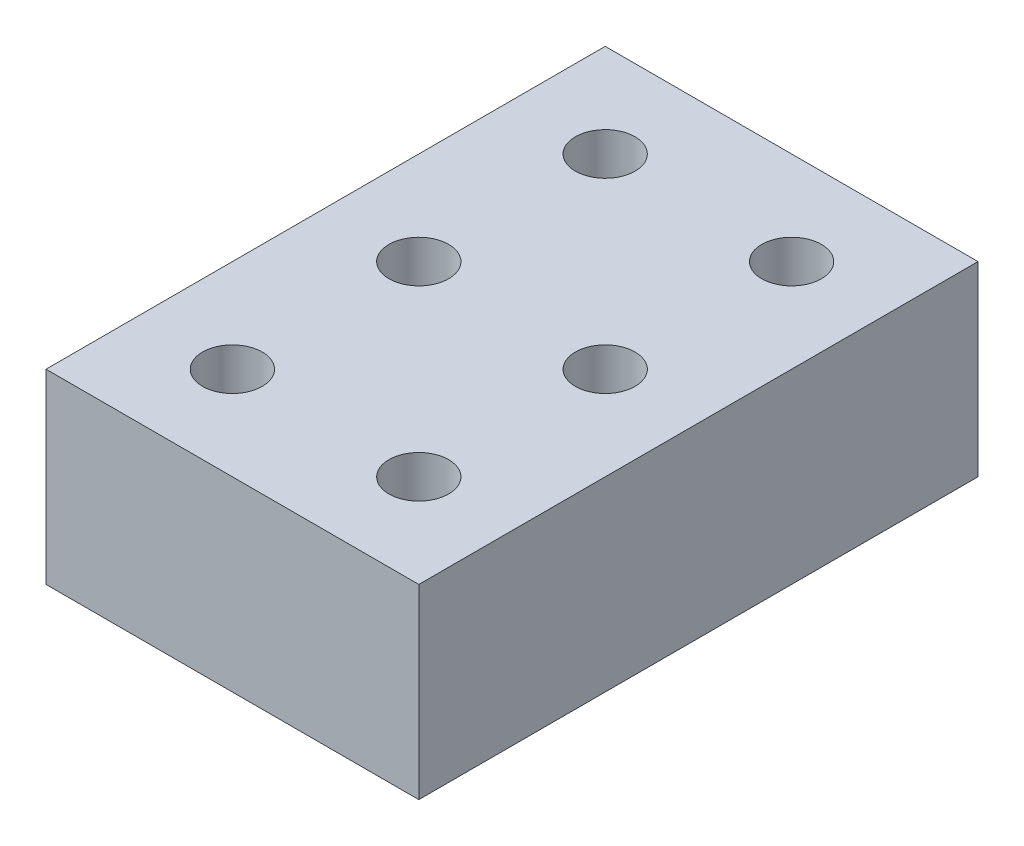
SolidWorks part; units mm, degrees
ref_plane "前视基准面" through (0, 0, 0) normal (0, 0, 1) x (1, 0, 0)
ref_plane "上视基准面" through (0, 0, 0) normal (0, 1, 0) x (1, 0, 0)
ref_plane "右视基准面" through (0, 0, 0) normal (1, 0, 0) x (0, 0, -1)
other "Configuration Table"
sketch "草图1" plane through (0, 0, 0) normal (0, 1, 0) x (1, 0, 0)
  line L0 (0, 0) -> (-10, 0) construction
  line L1 (-10, -15) -> (10, -15)
  line L2 (-10, -15) -> (-10, 15)
  line L3 (-10, 15) -> (10, 15)
  line L4 (10, -15) -> (10, 15)
  line L5 (-10, -15) -> (10, 15) construction
  line L6 (-10, 15) -> (10, -15) construction
  line L7 (0, 15) -> (0, -15) construction
  circle A0 centre (-5, 0) radius 1.6
  circle A1 centre (-5, 10) radius 1.6
  circle A2 centre (-5, -10) radius 1.6
  circle A3 centre (5, -10) radius 1.6
  circle A4 centre (5, 0) radius 1.6
  circle A5 centre (5, 10) radius 1.6
  point P0 (0, 0)
  dimension "D6" = 3.2
  dimension "D7" = 3.2
  dimension "D8" = 3.2
  dimension "D1" = 30
  dimension "D2" = 20
  dimension "D3" = 5
  dimension "D4" = 5
  dimension "D5" = 5
  dimension "D9" = 10
  dimension "D10" = 10
extrude "凸台-拉伸1" add sketch "草图1" along normal blind 10
